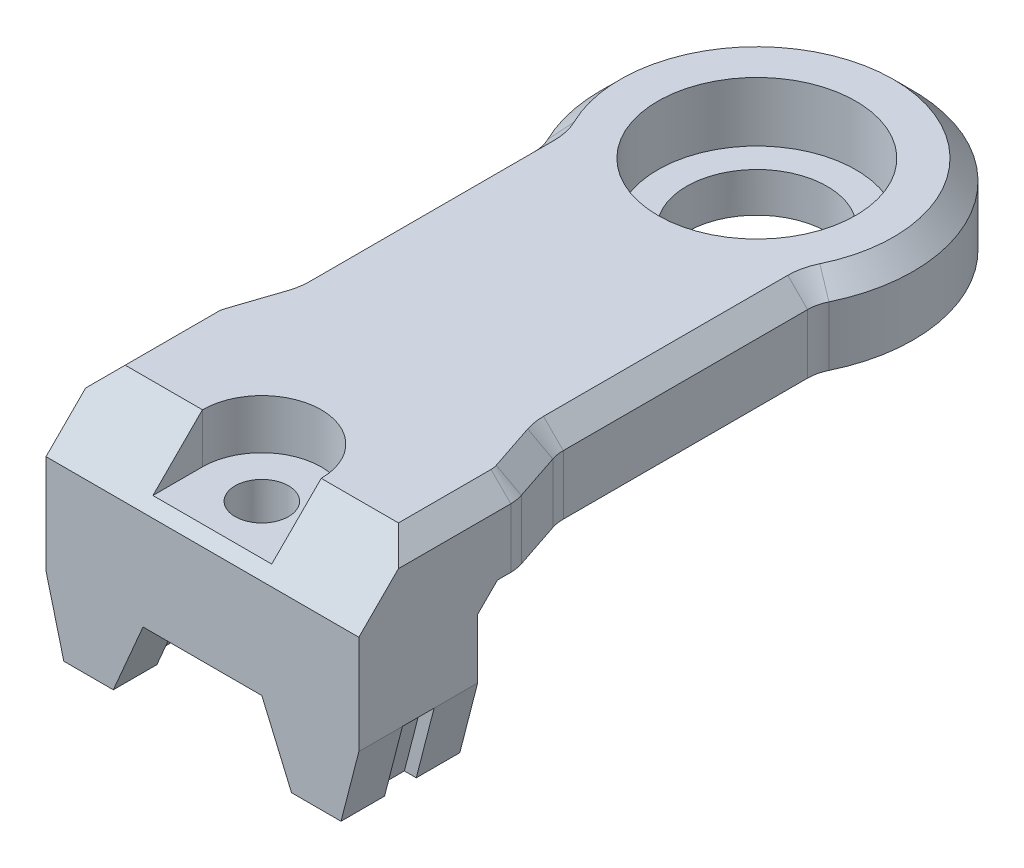
SolidWorks part; units mm, degrees
material "ABS"
ref_plane "正面" through (0, 0, 0) normal (0, 0, 1) x (1, 0, 0)
ref_plane "平面" through (0, 0, 0) normal (0, 1, 0) x (1, 0, 0)
ref_plane "右側面" through (0, 0, 0) normal (1, 0, 0) x (0, 0, -1)
sketch "ｽｹｯﾁ1" plane through (0, 0, 0) normal (0, 1, 0) x (1, 0, 0)
  line L2 (-7.9, 0) -> (-7.9, -28)
  line L3 (-7.9, -28) -> (7.9, -28)
  line L4 (7.9, 0) -> (7.9, -28)
  line L5 (-7.9, 0) -> (7.9, -28) construction
  line L6 (-7.9, -28) -> (7.9, 0) construction
  arc A0 (7.9, 0) -> (-7.9, 0) centre (0, 0) ccw
  point P7 (0, -14)
  dimension "D4" = 28
  dimension "D3" = 15.8
extrude "ﾎﾞｽ - 押し出し1" add sketch "ｽｹｯﾁ1" along normal blind 4
sketch "ｽｹｯﾁ4" plane through (0, 0, 28) normal (0, 0, 1) x (1, 0, 0)
  line L1 (-7, -7.5) -> (-4.5, -7.5)
  line L2 (-4.5, -7.5) -> (-3, -4)
  line L3 (-3, -4) -> (3, -4)
  line L4 (3, -4) -> (4.5, -7.5)
  line L5 (4.5, -7.5) -> (7, -7.5)
  line L7 (7.9, 0) -> (-7.9, 0)
  line L8 (-7, -7.5) -> (-7.9, -4)
  line L9 (-7.9, -4) -> (-7.9, 0)
  line L10 (7.9, 0) -> (7.9, -4)
  line L11 (7.9, -4) -> (7, -7.5)
  dimension "D1" = 7.5
  dimension "D2" = 3.5
  dimension "D3" = 3
  dimension "D4" = 7
  dimension "D5" = 2.5
  dimension "D9" = 4
  dimension "D10" = 4
extrude "ﾎﾞｽ - 押し出し3" add sketch "ｽｹｯﾁ4" against normal blind 6
chamfer "面取り1" distance 3 angle 45 1 edges at (0, 4, 28)
sketch "ｽｹｯﾁ6" plane through (0, 4, 0) normal (0, 1, 0) x (1, 0, 0)
  line L0 (-3, -25) -> (-3, -29)
  line L1 (-3, -29) -> (3, -29)
  line L2 (3, -29) -> (3, -25)
  line L3 (7.9, -28) -> (-7.9, -28) construction
  arc A0 (3, -25) -> (-3, -25) centre (0, -25) ccw
  dimension "D1" = 6
  dimension "D3" = 3
  dimension "D2" = 0
  dimension "D4" = 4
extrude "ｶｯﾄ - 押し出し2" cut sketch "ｽｹｯﾁ6" against normal blind 2.5
sketch "ｽｹｯﾁ7" plane through (0, 1.5, 0) normal (0, 1, 0) x (1, 0, 0)
  circle A0 centre (0, -25) radius 1.35
  dimension "D1" = 2.7
extrude "ｶｯﾄ - 押し出し3" cut sketch "ｽｹｯﾁ7" against normal up to next
sketch "ｽｹｯﾁ8" plane through (0, 0, 0) normal (0, -1, 0) x (1, 0, 0)
  circle A0 centre (0, 0) radius 6
  dimension "D1" = 12
extrude "ﾎﾞｽ - 押し出し4" add sketch "ｽｹｯﾁ8" along normal blind 1
fillet "ﾌｨﾚｯﾄ1" radius 0.5 1 edges at (0, 0, 6)
sketch "ｽｹｯﾁ9" plane through (0, 4, 0) normal (0, 1, 0) x (1, 0, 0)
  circle A0 centre (0, 0) radius 5
  dimension "D1" = 10
extrude "ｶｯﾄ - 押し出し4" cut sketch "ｽｹｯﾁ9" against normal blind 3
sketch "ｽｹｯﾁ10" plane through (0, 1, 0) normal (0, 1, 0) x (1, 0, 0)
  circle A0 centre (0, 0) radius 3.55
  dimension "D1" = 7.1
extrude "ｶｯﾄ - 押し出し5" cut sketch "ｽｹｯﾁ10" against normal blind 3.6
ref_plane "平面1" through (0, 0, 25) normal (0, 0, 1) x (1, 0, 0)
sketch "ｽｹｯﾁ11" plane through (0, 0, 25) normal (0, 0, 1) x (1, 0, 0)
  line L0 (3, -4) -> (4.5, -7.5)
  line L1 (3, -4) -> (3.6, -4)
  line L2 (4.5, -7.5) -> (5.1, -7.5)
  line L3 (3.6, -4) -> (5.1, -7.5)
  line L4 (3, -4) -> (5.1, -7.5) construction
  line L5 (4.5, -7.5) -> (3.6, -4) construction
  line L6 (-3, -4) -> (3, -4) construction
  line L7 (4.5, -7.5) -> (7, -7.5) construction
  line L8 (6.4, -7.5) -> (7, -7.5)
  line L9 (6.4, -7.5) -> (7.3, -4)
  line L10 (7, -7.5) -> (7.9, -4)
  line L11 (7.3, -4) -> (7.9, -4)
  line L12 (6.4, -7.5) -> (7.9, -4) construction
  line L13 (7, -7.5) -> (7.3, -4) construction
  point P5 (4.05, -5.75)
  point P18 (7.15, -5.75)
  dimension "D1" = 0.6
extrude "ｶｯﾄ - 押し出し6" cut sketch "ｽｹｯﾁ11" against normal mid plane 1.6
mirror "ﾐﾗｰ1" about plane through (0, 0, 0) normal (1, 0, 0) of "ｶｯﾄ - 押し出し6"
sketch "ｽｹｯﾁ12" plane through (0, 4, 0) normal (0, 1, 0) x (1, 0, 0)
  line L0 (-7.9, 0) -> (-7.9, -20)
  line L1 (-7.9, 0) -> (-7.9, -25) construction
  line L2 (-7.9, -20) -> (-6.9, -17)
  line L3 (-6.9, -17) -> (-6.9, -3.8471)
  line L4 (7.9, -28) -> (-7.9, -28) construction
  arc A0 (-7.9, 0) -> (-6.9, -3.8471) centre (0, 0) ccw
  arc A1 (7.9, 0) -> (-7.9, 0) centre (0, 0) ccw construction
  dimension "D1" = 6.9
  dimension "D2" = 3
  dimension "D3" = 11
extrude "ｶｯﾄ - 押し出し7" cut sketch "ｽｹｯﾁ12" against normal through all
mirror "ﾐﾗｰ2" about plane through (0, 0, 0) normal (1, 0, 0) of "ｶｯﾄ - 押し出し7"
fillet "ﾌｨﾚｯﾄ2" radius 2 6 edges at (6.9, 2, 3.8471) (6.9, 2, 17) (7.9, 2, 20) (-7.9, 2, 20) (-6.9, 2, 17) (-6.9, 2, 3.8471)
chamfer "面取り2" distance 1 angle 45 14 edges at (-7.9, 4, 22.6623) (0, 4, -7.9) (7.9, 4, 22.6623) (0, 0, 22) (-7.8742, 4, 20.0042) (-7.4, 4, 18.5) (-6.9258, 4, 16.9958) (-6.9, 4, 10.5057) (-6.9512, 4, 3.8864) (6.9512, 4, 3.8864) (6.9, 4, 10.5057) (6.9258, 4, 16.9958) (7.4, 4, 18.5) (7.8742, 4, 20.0042)
